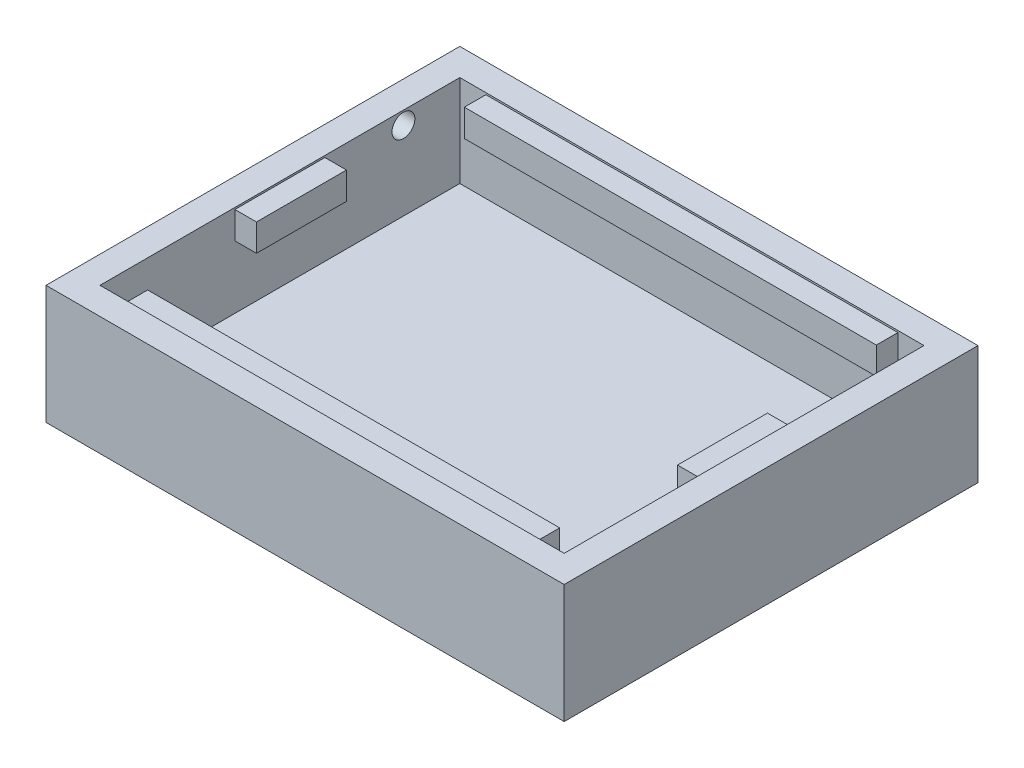
SolidWorks part; units mm, degrees
ref_plane "Front Plane" through (0, 0, 0) normal (0, 0, 1) x (1, 0, 0)
ref_plane "Top Plane" through (0, 0, 0) normal (0, 1, 0) x (1, 0, 0)
ref_plane "Right Plane" through (0, 0, 0) normal (1, 0, 0) x (0, 0, -1)
sketch "Sketch1" plane through (0, 0, 0) normal (0, 1, 0) x (1, 0, 0)
  line L1 (0, 0) -> (258, 0)
  line L2 (0, 0) -> (0, 200)
  line L3 (0, 200) -> (258, 200)
  line L4 (258, 0) -> (258, 200)
  line L5 (-15, -15) -> (273, -15)
  line L6 (-15, -15) -> (-15, 215)
  line L7 (-15, 215) -> (273, 215)
  line L8 (273, -15) -> (273, 215)
  point P9 (-15, 215)
  point P10 (-15, -15)
  dimension "D1" = 258
  dimension "D2" = 200
  dimension "D3" = 15
  dimension "D4" = 15
  dimension "D5" = 15
  dimension "D6" = 15
extrude "Walls" add sketch "Sketch1" along normal blind 51
sketch "Sketch3" plane through (0, 0, 0) normal (0, -1, 0) x (1, 0, 0)
  line L0 (273, -215) -> (-15, -215) construction
  line L1 (273, 15) -> (273, -215) construction
  line L2 (-15, 15) -> (273, 15) construction
  line L3 (-15, -215) -> (-15, 15) construction
  line L4 (273, -215) -> (-15, -215)
  line L5 (273, 15) -> (273, -215)
  line L6 (-15, 15) -> (273, 15)
  line L7 (-15, -215) -> (-15, 15)
extrude "Base" add sketch "Sketch3" along normal blind 15
ref_plane "Long_Support_Midplane" through (129, 0, 0) normal (1, 0, 0) x (0, 0, -1)
sketch "Sketch4" plane through (129, 0, 0) normal (1, 0, 0) x (0, 0, -1)
  line L1 (0, 50) -> (12, 50)
  line L2 (0, 50) -> (0, 34.9)
  line L3 (0, 34.9) -> (12, 34.9)
  line L4 (12, 50) -> (12, 34.9)
  line L6 (200, 50) -> (188, 50)
  line L7 (200, 50) -> (200, 34.9)
  line L8 (200, 34.9) -> (188, 34.9)
  line L9 (188, 50) -> (188, 34.9)
  line L14 (0, 0) -> (200, 0)
  line L15 (200, 0) -> (200, 51)
  line L16 (200, 51) -> (0, 51)
  line L17 (0, 51) -> (0, 0)
  line L18 (0, 0) -> (200, 0) construction
  line L19 (200, 0) -> (200, 51) construction
  line L20 (200, 51) -> (0, 51) construction
  line L21 (0, 51) -> (0, 0) construction
  point P10 (12, 50)
  dimension "D1" = 15.1
  dimension "D2" = 12
  dimension "D3" = 0
  dimension "D4" = 50
extrude "Long_Support" add sketch "Sketch4" along normal mid plane 229
ref_plane "Short_Support_Midplane" through (0, 0, -100) normal (0, 0, -1) x (-1, 0, 0)
sketch "Sketch5" plane through (0, 0, -100) normal (0, 0, -1) x (-1, 0, 0)
  line L1 (-258, 50) -> (-246, 50)
  line L2 (-258, 50) -> (-258, 34.9)
  line L3 (-258, 34.9) -> (-246, 34.9)
  line L4 (-246, 50) -> (-246, 34.9)
  line L5 (0, 50) -> (-12, 50)
  line L6 (0, 50) -> (0, 34.9)
  line L7 (0, 34.9) -> (-12, 34.9)
  line L8 (-12, 50) -> (-12, 34.9)
  line L12 (-258, 0) -> (0, 0)
  line L13 (0, 0) -> (0, 51)
  line L14 (0, 51) -> (-258, 51)
  line L15 (-258, 51) -> (-258, 0)
  line L16 (-258, 0) -> (0, 0) construction
  line L17 (0, 0) -> (0, 51) construction
  line L18 (0, 51) -> (-258, 51) construction
  line L19 (-258, 51) -> (-258, 0) construction
  point P10 (-279.6025, 23.7372)
  point P11 (-288.2256, 53.0556)
  dimension "D1" = 12
  dimension "D2" = 15.1
  dimension "D4" = 50
  dimension "D3" = 0
extrude "Short_Support" add sketch "Sketch5" along normal mid plane 50
sketch "Sketch6" plane through (0, 0, 0) normal (1, 0, 0) x (0, 0, -1)
  line L8 (200, 51) -> (0, 51)
  line L13 (0, 51) -> (0, 0)
  line L14 (0, 0) -> (200, 0)
  line L15 (200, 0) -> (200, 51)
  line L16 (200, 51) -> (0, 51) construction
  line L21 (0, 51) -> (0, 0) construction
  line L22 (0, 0) -> (200, 0) construction
  line L23 (200, 0) -> (200, 51) construction
  circle A0 centre (168.65, 43.65) radius 6.35
  point P3 (168.65, 40.2673)
  point P4 (168.6053, 29.7594)
  point P6 (168.65, 42.2545)
  dimension "D2" = 12.7
  dimension "D4" = 43.65
  dimension "D3" = 31.35
  dimension "D1" = 0
extrude "Cut-Extrude4" cut sketch "Sketch6" against normal up to next
